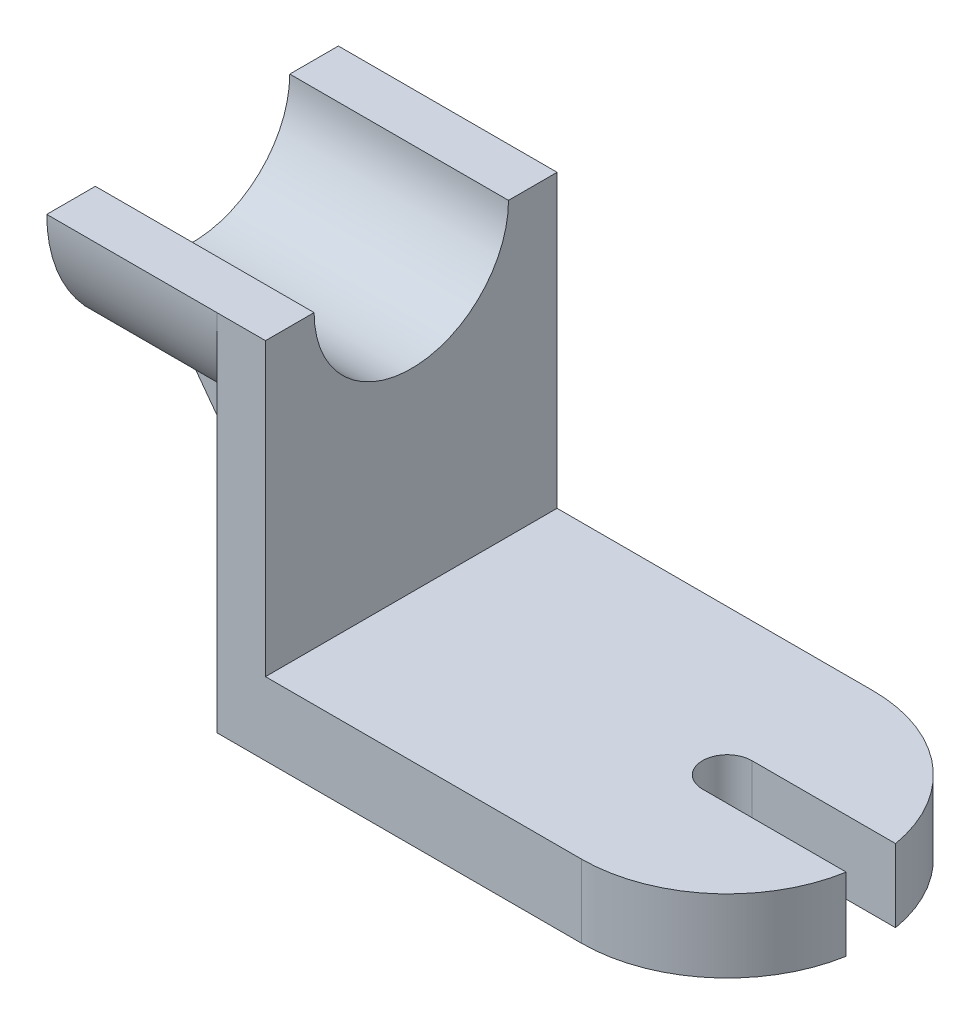
SolidWorks part; units mm, degrees
ref_plane "Front Plane" through (0, 0, 0) normal (0, 0, 1) x (1, 0, 0)
ref_plane "Top Plane" through (0, 0, 0) normal (0, 1, 0) x (1, 0, 0)
ref_plane "Right Plane" through (0, 0, 0) normal (1, 0, 0) x (0, 0, -1)
sketch "Sketch1" plane through (0, 0, 0) normal (0, 1, 0) x (1, 0, 0)
  line L0 (95.25, -12.9029) -> (95.25, 12.9029)
  line L1 (-95.25, -76.2) -> (95.25, -76.2)
  line L2 (-95.25, -76.2) -> (-95.25, 76.2)
  line L3 (-95.25, 76.2) -> (95.25, 76.2)
  line L5 (95.25, 12.9029) -> (170.3496, 12.9029)
  line L8 (95.25, -12.9029) -> (170.3496, -12.9029)
  arc A0 (95.25, -76.2) -> (170.3496, -12.9029) centre (95.25, 0) ccw
  arc A1 (170.3496, 12.9029) -> (95.25, 76.2) centre (95.25, 0) ccw
  point P0 (0, 0)
  dimension "D1" = 152.4
  dimension "D2" = 190.5
extrude "Boss-Extrude1" add sketch "Sketch1" along normal blind 38.1
ref_plane "Plane1" through (-95.25, 0, 0) normal (-1, 0, 0) x (0, 0, 1)
sketch "Sketch2" plane through (-95.25, 0, 0) normal (-1, 0, 0) x (0, 0, 1)
  line L0 (-76.2, 0) -> (-76.2, 190.1842)
  line L1 (-76.2, 190.1842) -> (76.2, 190.1842)
  line L2 (76.2, 190.1842) -> (76.2, 0)
  line L3 (76.2, 0) -> (-76.2, 0)
extrude "Boss-Extrude2" add sketch "Sketch2" against normal blind 25.4
ref_plane "Plane3" through (0, 190.1842, 0) normal (0, 1, 0) x (1, 0, 0)
sketch "Sketch6" plane through (0, 190.1842, 0) normal (0, 1, 0) x (1, 0, 0)
  line L0 (0, 0) -> (-262.5345, 0) construction
  line L1 (-95.25, 76.2) -> (-184.1632, 76.2)
  line L2 (-184.1632, 76.2) -> (-184.1632, 50.8)
  line L3 (-184.1632, 50.8) -> (-95.25, 50.8)
  line L4 (-95.25, -76.2) -> (-95.25, 76.2) construction
  line L5 (-95.25, 76.2) -> (-95.25, 50.8)
  dimension "D1" = 25.4
  dimension "D2" = 88.9132
revolve "Revolve1" add sketch "Sketch6" angle 180 about L0
sketch "Sketch7" plane through (-95.25, 0, 0) normal (-1, 0, 0) x (0, 0, 1)
  line L0 (0, 0) -> (0, 271.6209) construction
  line L1 (12.9029, 0) -> (-12.9029, 0)
  line L2 (-12.9029, 0) -> (-12.9029, 115.0845)
  line L3 (-12.9029, 115.0845) -> (0, 113.9842)
  line L4 (12.9029, 115.0845) -> (0, 113.9842)
  line L5 (12.9029, 0) -> (12.9029, 115.0845)
  arc A0 (-76.2, 190.1842) -> (76.2, 190.1842) centre (0, 190.1842) ccw construction
extrude "Boss-Extrude3" add sketch "Sketch7" along normal blind 88.9
sketch "Sketch8" plane through (0, 0, 12.9029) normal (0, 0, 1) x (1, 0, 0)
  line L0 (-98.8901, 0) -> (-184.15, 0)
  line L1 (-184.15, 0) -> (-95.25, 0) construction
  line L2 (-184.15, 0) -> (-184.15, 115.0845)
  line L3 (-184.15, 115.0845) -> (-98.8901, 0)
extrude "Cut-Extrude1" cut sketch "Sketch8" against normal blind 88.9
sketch "Sketch9" plane through (0, 38.1, 0) normal (0, 1, 0) x (1, 0, 0)
  line L0 (95.25, -12.9029) -> (95.25, 12.9029) construction
  circle A0 centre (95.25, 0) radius 12.9029
extrude "Cut-Extrude2" cut sketch "Sketch9" against normal blind 88.9
sketch "Sketch11" plane through (-95.25, 0, 0) normal (-1, 0, 0) x (0, 0, 1)
  line L0 (50.8, 190.1842) -> (-50.8, 190.1842) construction
  circle A0 centre (0, 190.1842) radius 50.8
extrude "Cut-Extrude3" cut sketch "Sketch11" against normal blind 30.48
